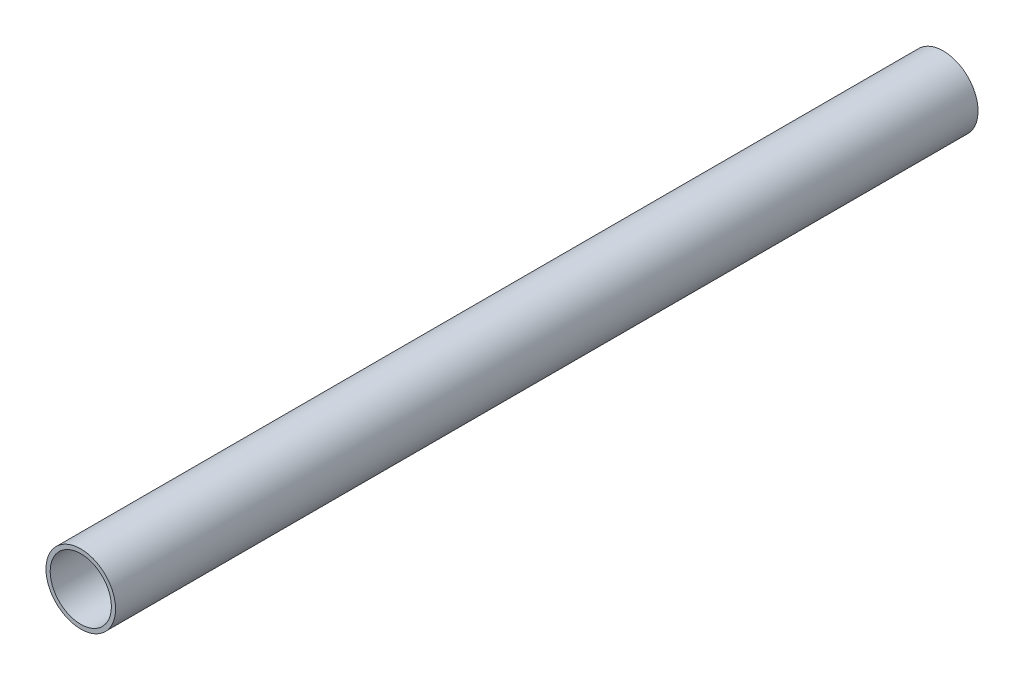
SolidWorks part; units mm, degrees
material "3k Carbon Fiber"
ref_plane "Front Plane" through (0, 0, 0) normal (0, 0, 1) x (1, 0, 0)
ref_plane "Top Plane" through (0, 0, 0) normal (0, 1, 0) x (1, 0, 0)
ref_plane "Right Plane" through (0, 0, 0) normal (1, 0, 0) x (0, 0, -1)
sketch "Sketch1" plane through (0, 0, 0) normal (0, 0, 1) x (1, 0, 0)
  circle A0 centre (0, 0) radius 12.5
  circle A1 centre (0, 0) radius 11
  dimension "D1" = 25
  dimension "D2" = 22
extrude "Boss-Extrude1" add sketch "Sketch1" along normal blind 500
sketch "Sketch3" plane through (0, 0, 0) normal (0, 0, -1) x (-1, 0, 0)
  circle A0 centre (0, 0) radius 11
  circle A1 centre (0, 0) radius 12.5
extrude "Cut-Extrude2" cut sketch "Sketch3" against normal blind 190
